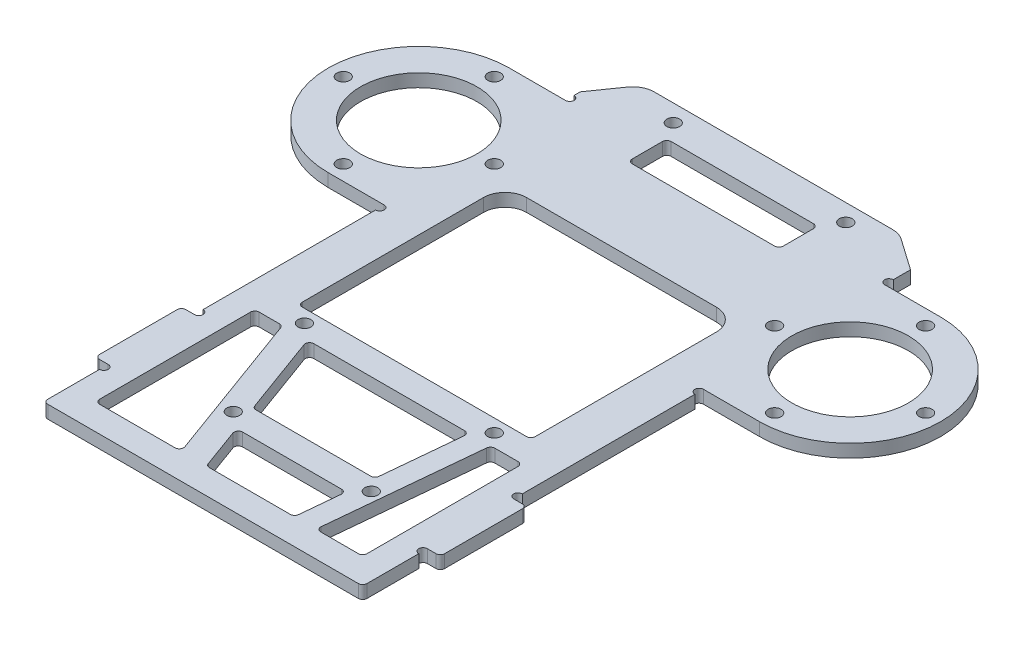
SolidWorks part; units mm, degrees
material "Thornel Mat VMA"
ref_plane "前视基准面" through (0, 0, 0) normal (0, 0, 1) x (1, 0, 0)
ref_plane "上视基准面" through (0, 0, 0) normal (0, 1, 0) x (1, 0, 0)
ref_plane "右视基准面" through (0, 0, 0) normal (1, 0, 0) x (0, 0, -1)
sketch "草图1" plane through (0, 0, 0) normal (0, 1, 0) x (1, 0, 0)
  line L14 (-50, 0) -> (0, 0) construction
  line L71 (-37, 21) -> (-50, 21)
  line L73 (37, 33) -> (-37, 33)
  line L74 (-37, 33) -> (-37, 21)
  line L78 (0, -1.65) -> (0, 1.65) construction
  line L81 (37, 33) -> (37, 21)
  line L144 (-37, -65) -> (-37, -21)
  line L145 (37, -65) -> (37, -21)
  line L203 (-67.5, 0) -> (-50, 0) construction
  line L204 (-37, -21) -> (-50, -21)
  line L206 (37, -21) -> (50, -21)
  line L228 (37, 21) -> (50, 21)
  line L230 (40, -65) -> (40, -85)
  line L235 (-37, -65) -> (-40, -65)
  line L238 (-37, -85) -> (-37, -100)
  line L242 (37, -100) -> (-37, -100)
  line L244 (-22.5, -54) -> (-13, -80) construction
  line L245 (-13, -80) -> (19, -80) construction
  line L246 (19, -80) -> (21.5, -54) construction
  line L247 (21.5, -54) -> (-22.5, -54) construction
  line L248 (-37, -85) -> (-40, -85)
  line L249 (-40, -65) -> (-40, -85)
  line L250 (37, -85) -> (40, -85)
  line L251 (37, -85) -> (37, -100)
  line L252 (37, -65) -> (40, -65)
  circle A0 centre (-50, 0) radius 13.5
  circle A41 centre (50, 0) radius 13.5
  circle A52 centre (-50, 17.5) radius 1.5
  circle A65 centre (-32.5, 0) radius 1.5
  circle A81 centre (-67.5, 0) radius 1.5
  circle A82 centre (-50, 0) radius 17.5 construction
  circle A83 centre (-50, -17.5) radius 1.5
  circle A84 centre (32.5, 0) radius 1.5
  circle A85 centre (50, -17.5) radius 1.5
  circle A86 centre (50, 17.5) radius 1.5
  circle A87 centre (50, 0) radius 17.5 construction
  circle A88 centre (67.5, 0) radius 1.5
  arc A95 (-50, 21) -> (-50, -21) centre (-50, 0) ccw
  arc A104 (50, 21) -> (50, -21) centre (50, 0) cw
  circle A105 centre (-20, 29) radius 1.5
  circle A106 centre (20, 29) radius 1.5
  circle A107 centre (21.5, -54) radius 1.5
  circle A108 centre (-13, -80) radius 1.5
  circle A109 centre (19, -80) radius 1.5
  circle A110 centre (-22.5, -54) radius 1.5
  dimension "D2" = 33
  dimension "D3" = 50
  dimension "D7" = 27
  dimension "D8" = 14.5
  dimension "D10" = 3
  dimension "D12" = 40
  dimension "D15" = 20
  dimension "D16" = 4
  dimension "D6" = 20
  dimension "D9" = 44
  dimension "D43" = 3
  dimension "D44" = 35
  dimension "D74" = 3
  dimension "D13" = 21
  dimension "D5" = 26
  dimension "D11" = 3
  dimension "D14" = 15
  dimension "D17" = 74
  dimension "D31" = 100
  dimension "D40" = 32
  dimension "D42" = 0
  dimension "D71" = 9.5
  dimension "D46" = 2
  dimension "D45" = 4
extrude "凸台-拉伸1" add sketch "草图1" along normal blind 3
sketch "草图3" plane through (0, 3, 0) normal (0, 1, 0) x (1, 0, 0)
  line L23 (0, -1.65) -> (0, 1.65) construction
  line L28 (-27, -3) -> (27, -3)
  line L29 (-27, -3) -> (-27, -51)
  line L30 (-27, -51) -> (27, -51)
  line L32 (27, -3) -> (27, -51)
  line L33 (-37, -21) -> (-37, -65) construction
  line L34 (17.5, 25) -> (17.5, 16)
  line L35 (-17.5, 25) -> (17.5, 25)
  line L36 (-17.5, 25) -> (-17.5, 16)
  line L37 (-17.5, 16) -> (17.5, 16)
  line L39 (37, 33) -> (-37, 33) construction
  line L40 (-22.5, -54) -> (-13, -80) construction
  line L41 (19, -80) -> (21.5, -54) construction
  line L42 (-24.5978, -57) -> (-11.0786, -94)
  line L43 (-18.7422, -57) -> (18.7, -57)
  line L44 (-18.7422, -57) -> (-11.4345, -77)
  line L45 (-11.4345, -77) -> (16.7769, -77)
  line L46 (18.7, -57) -> (16.7769, -77)
  line L47 (-11.0786, -94) -> (-31, -94)
  line L48 (-31, -94) -> (-31, -57)
  line L49 (-24.5978, -57) -> (-31, -57)
  line L50 (-9.2422, -83) -> (-5.223, -94)
  line L51 (-5.223, -94) -> (15.1423, -94)
  line L52 (15.1423, -94) -> (16.2, -83)
  line L53 (16.2, -83) -> (-9.2422, -83)
  line L54 (-37, -85) -> (-37, -100) construction
  line L55 (-37, -100) -> (37, -100) construction
  line L56 (23.7231, -57) -> (20.1654, -94)
  line L57 (20.1654, -94) -> (31, -94)
  line L58 (31, -94) -> (31, -57)
  line L59 (31, -57) -> (23.7231, -57)
  line L60 (37, -65) -> (37, -21) construction
  circle A5 centre (-22.5, -54) radius 1.5 construction
  circle A6 centre (-13, -80) radius 1.5 construction
  point P49 (22.7185, -57)
  point P50 (-11.4345, -94)
  dimension "D9" = 3
  dimension "D13" = 6
  dimension "D2" = 3
  dimension "D10" = 3
  dimension "D14" = 3
  dimension "D1" = 8
  dimension "D3" = 48
  dimension "D4" = 10
  dimension "D5" = 35
  dimension "D6" = 9
  dimension "D7" = 2.5
  dimension "D8" = 2.5
  dimension "D11" = 3
  dimension "D12" = 6
  dimension "D15" = 2.5
  dimension "D16" = 6
extrude "切除-拉伸2" cut sketch "草图3" against normal through all
sketch "草图2" plane through (0, 3, 0) normal (0, 1, 0) x (1, 0, 0)
  line L0 (-37, 33) -> (-37, 21) construction
  line L1 (-37, -21) -> (-37, -65) construction
  line L2 (-37, -21) -> (-37, -65) construction
  line L3 (-37, -85) -> (-37, -100) construction
  line L10 (0, -1.65) -> (0, 1.65) construction
  circle A4 centre (-37, 22) radius 1
  circle A5 centre (-37, -22) radius 1
  circle A6 centre (-37, -64) radius 1
  circle A7 centre (-37, -86) radius 1
  circle A16 centre (37, -86) radius 1
  circle A17 centre (37, -64) radius 1
  circle A18 centre (37, -22) radius 1
  circle A19 centre (37, 22) radius 1
  dimension "D1" = 2
extrude "切除-拉伸1" cut sketch "草图2" against normal through all
chamfer "倒角1" distance 6 angle 55 2 edges at (37, 1.5, -33) (-37, 1.5, -33)
fillet "圆角1" radius 1 28 edges at (37, 1.5, 100) (-37, 1.5, 100) (40, 1.5, 65) (40, 1.5, 85) (-40, 1.5, 65) (-27, 1.5, 51) (-40, 1.5, 85) (-31, 1.5, 57) (-24.5978, 1.5, 57) (-11.0786, 1.5, 94) (-31, 1.5, 94) (-18.7422, 1.5, 57) (18.7, 1.5, 57) (16.7769, 1.5, 77) (-11.4345, 1.5, 77) (16.2, 1.5, 83) (15.1423, 1.5, 94) (-9.2422, 1.5, 83) (-5.223, 1.5, 94) (31, 1.5, 57) (31, 1.5, 94) (23.7231, 1.5, 57) (20.1654, 1.5, 94) (27, 1.5, 51) (-17.5, 1.5, -25) (17.5, 1.5, -25) (17.5, 1.5, -16) (-17.5, 1.5, -16)
fillet "圆角2" radius 5 4 edges at (-31, 1.5, -33) (28.4311, 1.5, -33) (27, 1.5, 3) (-27, 1.5, 3)
